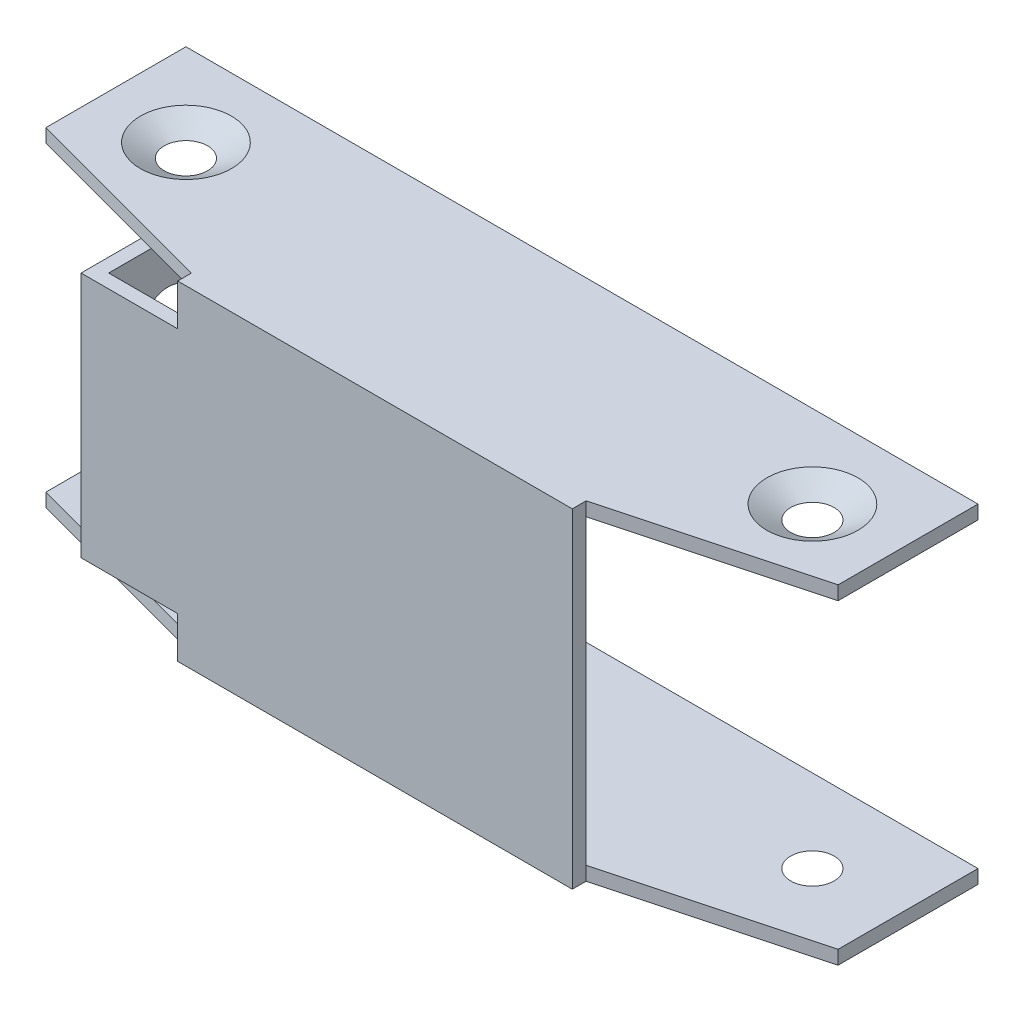
SolidWorks part; units mm, degrees
ref_plane "Front Plane" through (0, 0, 0) normal (0, 0, 1) x (1, 0, 0)
ref_plane "Top Plane" through (0, 0, 0) normal (0, 1, 0) x (1, 0, 0)
ref_plane "Right Plane" through (0, 0, 0) normal (1, 0, 0) x (0, 0, -1)
sketch "Sketch1" plane through (0, 0, 0) normal (0, 1, 0) x (1, 0, 0)
  line L0 (0, 16.5687) -> (0, -18.8099) construction
  line L1 (-26.8408, 0) -> (30.7895, 0) construction
  line L3 (-36.449, 9.525) -> (36.449, 9.525)
  line L4 (-36.449, 9.525) -> (-36.449, -9.525)
  line L5 (-36.449, -9.525) -> (36.449, -9.525)
  line L6 (36.449, 9.525) -> (36.449, -9.525)
  line L7 (-36.449, 9.525) -> (36.449, -9.525) construction
  line L8 (-36.449, -9.525) -> (36.449, 9.525) construction
  circle A0 centre (-28.829, 1.905) radius 4.191
  circle A1 centre (28.829, 1.905) radius 4.191
  point P5 (0, 0)
  point P14 (0, 0)
  point P15 (0, 0)
  point P16 (28.829, 3.1175)
  dimension "D4" = 8.382
  dimension "D1" = 7.62
  dimension "D2" = 19.05
  dimension "D3" = 57.658
  dimension "D5" = 7.62
extrude "Boss-Extrude1" add sketch "Sketch1" along normal blind 1.27 contours A0 | A1 | L6 L3 L4 L5 A1 A0
ref_plane "Plane1" through (0, 0, 0) normal (-1, 0, 0) x (0, 0, 1)
sketch "Sketch6" plane through (0, 0, 0) normal (0, -1, 0) x (1, 0, 0)
  line L0 (-36.449, -9.525) -> (-36.449, 9.525) construction
  line L6 (0, 17.7337) -> (0, -24.001) construction
  line L7 (-45.7625, -18.8385) -> (-12.5585, 14.3655) construction
  circle A0 centre (-28.829, -1.905) radius 4.191
  circle A1 centre (28.829, -1.905) radius 4.191
  point P11 (0, 0)
  dimension "D2" = 8.382
  dimension "D3" = 57.658
  dimension "D4" = 135
extrude "Cut-Extrude1" cut sketch "Sketch6" against normal blind 25.4 draft 60
sketch "Sketch7" plane through (0, 1.27, 0) normal (0, 1, 0) x (1, 0, 0)
  line L0 (36.449, 9.525) -> (36.449, -9.525) construction
  line L1 (-36.449, -9.525) -> (36.449, -9.525)
  line L2 (-36.449, -9.525) -> (-36.449, -8.255)
  line L3 (-36.449, -8.255) -> (36.449, -8.255)
  line L4 (36.449, -9.525) -> (36.449, -8.255)
  dimension "D1" = 1.27
extrude "Boss-Extrude4" add sketch "Sketch7" along normal blind 30.48
sketch "Sketch8" plane through (0, 0, 0) normal (0, -1, 0) x (1, 0, 0)
  line L0 (-36.449, 3.3547) -> (-18.161, 8.255)
  line L1 (-36.449, -9.525) -> (-36.449, 9.525) construction
  line L2 (-18.161, 8.255) -> (-18.161, 9.525)
  line L3 (-36.449, 9.525) -> (36.449, 9.525) construction
  line M6 (36.449, 9.525) -> (-36.449, 9.525)
  line M7 (-36.449, 9.525) -> (-36.449, -9.525)
  dimension "D1" = 15
  dimension "D2" = 18.288
  dimension "D3" = 1.27
extrude "Cut-Extrude2" cut sketch "Sketch8" against normal through all both and the other way through all contours L0 L2 M6 M7
mirror "Mirror2" about plane through (0, 0, 0) normal (-1, 0, 0) of "Cut-Extrude2"
sketch "Sketch10" plane through (-18.161, 0, 0) normal (-1, 0, 0) x (0, 0, 1)
  line L0 (8.255, 31.75) -> (8.255, 1.27) construction
  line L1 (9.525, 31.75) -> (8.255, 31.75)
  line L2 (9.525, 31.75) -> (9.525, 3.81)
  line L3 (9.525, 3.81) -> (8.255, 3.81)
  line L4 (8.255, 31.75) -> (8.255, 3.81)
  line L5 (8.255, 1.27) -> (3.3547, 1.27) construction
  dimension "D1" = 2.54
extrude "Boss-Extrude5" add sketch "Sketch10" along normal blind 8.89
sketch "Sketch11" plane through (0, 0, 8.255) normal (0, 0, -1) x (-1, 0, 0)
  line L0 (27.051, 3.81) -> (18.161, 3.81) construction
  line L1 (27.051, 31.75) -> (25.781, 31.75)
  line L2 (27.051, 31.75) -> (27.051, 3.81)
  line L3 (27.051, 3.81) -> (25.781, 3.81)
  line L4 (25.781, 31.75) -> (25.781, 3.81)
  dimension "D1" = 1.27
extrude "Boss-Extrude6" add sketch "Sketch11" along normal blind 11.43
sketch "Sketch12" plane through (-27.051, 0, 0) normal (-1, 0, 0) x (0, 0, 1)
  line L1 (8.255, 3.81) -> (8.255, 1.27) construction
  line L2 (-3.175, 3.81) -> (9.525, 3.81) construction
  circle A0 centre (2.7788, 10.16) radius 2.5
  circle A1 centre (2.7788, 20.16) radius 2.5
  point P8 (2.7788, 23.208)
  point P9 (0, 0)
  dimension "D1" = 6.35
  dimension "D2" = 5
  dimension "D4" = 5
  dimension "D3" = 5.4762
  dimension "D5" = 10
extrude "Cut-Extrude3" cut sketch "Sketch12" against normal through all
sketch "Sketch14" plane through (-27.051, 0, 0) normal (-1, 0, 0) x (0, 0, 1)
  line L0 (9.525, 3.81) -> (9.525, 31.75) construction
  line L1 (-3.175, 31.75) -> (9.525, 31.75)
  line L2 (-3.175, 31.75) -> (-3.175, 26.51)
  line L3 (-3.175, 26.51) -> (9.525, 26.51)
  line L4 (9.525, 31.75) -> (9.525, 26.51)
  line L5 (2.7788, 20.16) -> (-9.9747, 20.16) construction
  line M8 (9.525, 3.81) -> (9.525, 31.75)
  line M9 (9.525, 31.75) -> (-3.175, 31.75)
  line M10 (-3.175, 31.75) -> (-3.175, 3.81)
  dimension "D1" = 6.35
extrude "Cut-Extrude5" cut sketch "Sketch14" against normal through all both and the other way through all contours L3 M10 M8 M9
sketch "Sketch15" plane through (0, 26.51, 0) normal (0, 1, 0) x (1, 0, 0)
  line L1 (-18.161, -8.255) -> (18.161, -8.255)
  line L2 (-18.161, -8.255) -> (-18.161, -9.525)
  line L3 (-18.161, -9.525) -> (18.161, -9.525)
  line L4 (18.161, -8.255) -> (18.161, -9.525)
extrude "Boss-Extrude8" add sketch "Sketch15" along normal blind 3.81
sketch "Sketch16" plane through (0, 1.27, 0) normal (0, 1, 0) x (1, 0, 0)
  line L0 (-36.449, 9.525) -> (-36.449, -3.3547)
  line L1 (-36.449, 9.525) -> (-36.449, -3.3547) construction
  line L2 (-36.449, -3.3547) -> (-18.161, -8.255)
  line L3 (-18.161, -8.255) -> (-18.161, -9.525)
  line L4 (-18.161, -9.525) -> (18.161, -9.525)
  line L5 (18.161, -9.525) -> (18.161, -8.255)
  line L6 (18.161, -8.255) -> (36.449, -3.3547)
  line L7 (36.449, -3.3547) -> (36.449, 9.525)
  line L8 (36.449, 9.525) -> (-36.449, 9.525)
  point P5 (-36.449, -3.3547)
extrude "Boss-Extrude9" add sketch "Sketch16" against normal blind 1.27 from surface at 29.05 starting at face at (0, 30.32, 8.89)
sketch "Sketch17" plane through (0, 30.32, 0) normal (0, 1, 0) x (1, 0, 0)
  circle A0 centre (-28.829, 1.905) radius 4.191
  circle A1 centre (28.829, 1.905) radius 4.191
  circle A2 centre (-28.829, 1.905) radius 4.191 construction
extrude "Cut-Extrude6" cut sketch "Sketch17" against normal blind 1.27 draft 60
